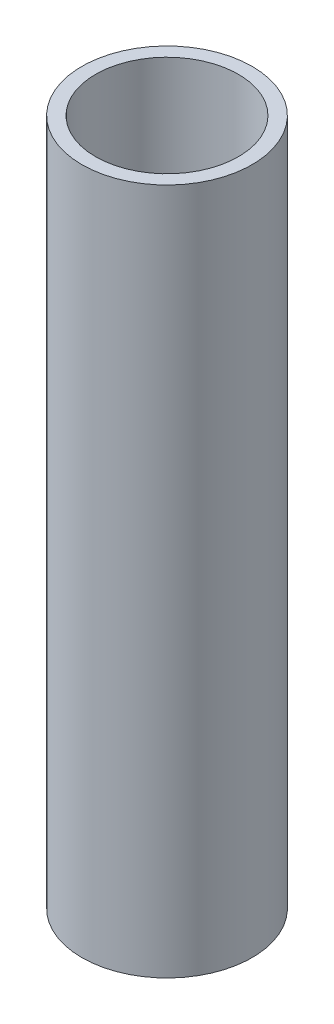
SolidWorks part; units mm, degrees
material "PC High Viscosity"
ref_plane "Front Plane" through (0, 0, 0) normal (0, 0, 1) x (1, 0, 0)
ref_plane "Top Plane" through (0, 0, 0) normal (0, 1, 0) x (1, 0, 0)
ref_plane "Right Plane" through (0, 0, 0) normal (1, 0, 0) x (0, 0, -1)
sketch "Sketch1" plane through (0, 0, 0) normal (0, 1, 0) x (1, 0, 0)
  circle A0 centre (0, 0) radius 12.4
  circle A1 centre (0, 0) radius 10.4
  dimension "D1" = 24.8
  dimension "D2" = 2
extrude "Boss-Extrude1" add sketch "Sketch1" along normal blind 100
